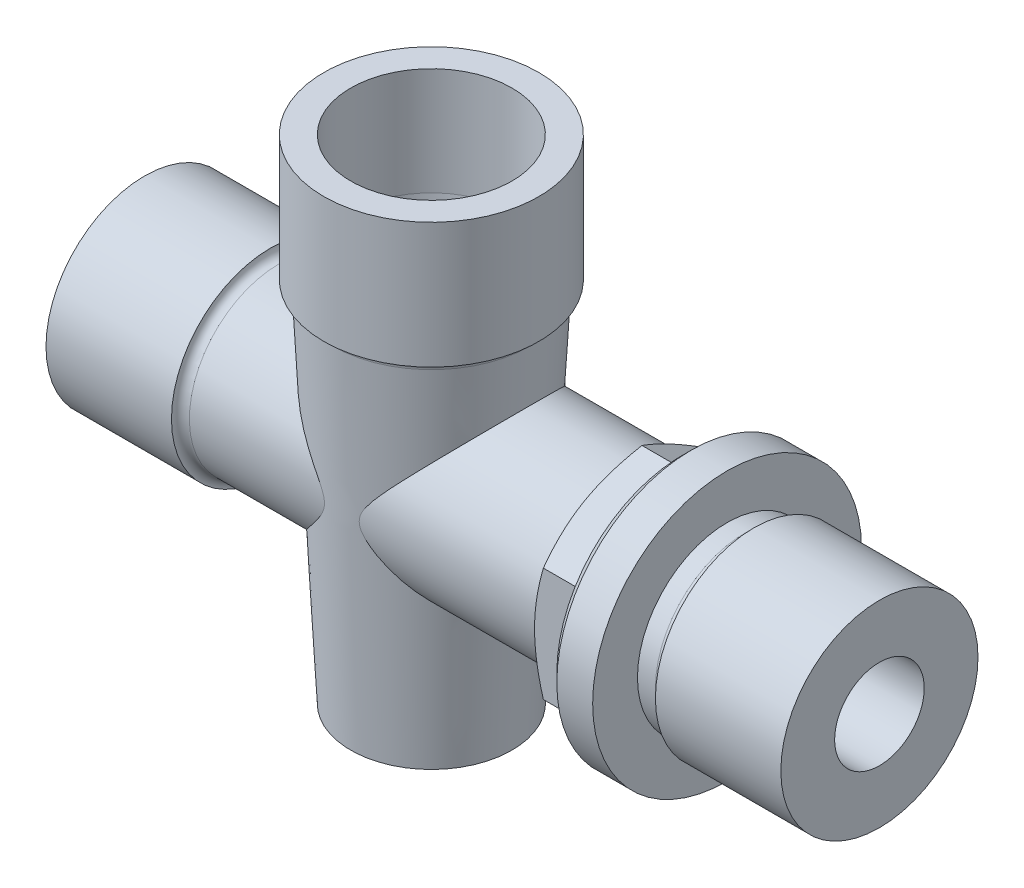
SolidWorks part; units mm, degrees
ref_plane "Спереди" through (0, 0, 0) normal (0, 0, 1) x (1, 0, 0)
ref_plane "Сверху" through (0, 0, 0) normal (0, 1, 0) x (1, 0, 0)
ref_plane "Справа" through (0, 0, 0) normal (1, 0, 0) x (0, 0, -1)
sketch "Эскиз1" plane through (0, 0, 0) normal (0, 0, 1) x (1, 0, 0)
  line L0 (0, 0) -> (0, 55) construction
  line L1 (0, 0) -> (-9, 0)
  line L2 (0, 55) -> (-9, 55) construction
  line L3 (-9, 55) -> (-12, 55)
  line L4 (-12, 55) -> (-12, 41)
  line L6 (-9, 55) -> (-9, 43)
  line L7 (0, 0) -> (0, 5)
  line L8 (-12, 41) -> (-12, 39.8607) construction
  line L9 (0, 5) -> (-7.5, 5)
  line L10 (-7.5, 5) -> (-7.5, 7)
  line L11 (-7.5, 7) -> (-5.5, 7)
  line L12 (-9, 43) -> (-5.5, 7)
  line L13 (-12, 41) -> (-12, 40) construction
  line L14 (-9, 0) -> (-11.0012, 40.0499)
  arc A0 (-11.0012, 40.0499) -> (-12, 41) centre (-12, 40) ccw
  dimension "D5" = 36
  dimension "D6" = 7.5
  dimension "D7" = 2
  dimension "D8" = 9
  dimension "D9" = 5
  dimension "D10" = 2
  dimension "D11" = 2
  dimension "D1" = 9
  dimension "D2" = 14
  dimension "D3" = 12
  dimension "D4" = 12
revolve "Повернуть1" add sketch "Эскиз1" angle 360 about L0
sketch "Эскиз2" plane through (0, 0, 0) normal (0, 0, 1) x (1, 0, 0)
  line L0 (0, 0) -> (-12.0052, 0) construction
  line L1 (0, 24) -> (-32, 24) construction
  line L2 (0, 0) -> (0, 55) construction
  line L3 (-9, 0) -> (-11.0012, 40.0499) construction
  line L4 (-32, 19) -> (0, 19)
  line L5 (-32, 24) -> (-32, 19) construction
  line L6 (-32, 19) -> (-32, 13)
  line L7 (-32, 13) -> (-18, 13)
  line L8 (-18, 13) -> (-17, 13) construction
  line L9 (-17, 14) -> (0, 14)
  line L10 (0, 14) -> (0, 19)
  arc A0 (-17, 14) -> (-18, 13) centre (-17, 13) ccw
  point P11 (-10.1993, 24)
  dimension "D5" = 11
  dimension "D6" = 1
  dimension "D1" = 24
  dimension "D2" = 32
  dimension "D3" = 5
  dimension "D4" = 14
revolve "Повернуть2" add sketch "Эскиз2" angle 360 about L1
sketch "Эскиз3" plane through (0, 0, 0) normal (0, 0, 1) x (1, 0, 0)
  line L0 (0, 0) -> (0, 24) construction
  line L1 (0, 24) -> (50, 24) construction
  line L2 (50, 24) -> (50, 29) construction
  line L3 (50, 29) -> (50, 35)
  line L4 (50, 35) -> (36, 35)
  line L5 (50, 29) -> (0, 29)
  line L6 (0, 0) -> (0, 55) construction
  line L7 (36, 35) -> (35, 35) construction
  line L8 (35, 34) -> (33, 34)
  line L9 (33, 34) -> (33, 39)
  line L10 (33, 39) -> (29, 39)
  line L11 (29, 39) -> (28, 38)
  line L12 (28, 38) -> (28, 34)
  line L13 (28, 34) -> (0, 34)
  line L14 (0, 34) -> (0, 29)
  arc A0 (35, 34) -> (36, 35) centre (35, 35) ccw
  dimension "D5" = 2
  dimension "D6" = 17
  dimension "D1" = 50
  dimension "D2" = 5
  dimension "D3" = 11
  dimension "D4" = 14
  dimension "D7" = 30
  dimension "D8" = 45
  dimension "D9" = 4
  dimension "D10" = 1
revolve "Повернуть3" add sketch "Эскиз3" angle 360 about L1
sketch "Эскиз4" plane through (28, 0, 0) normal (-1, 0, 0) x (0, 0, 1)
  line L1 (0, 36.7017) -> (-11, 30.3509)
  line L2 (-11, 30.3509) -> (-11, 17.6491)
  line L3 (-11, 17.6491) -> (0, 11.2983)
  line L4 (0, 11.2983) -> (11, 17.6491)
  line L5 (11, 17.6491) -> (11, 30.3509)
  line L6 (11, 30.3509) -> (0, 36.7017)
  circle A0 centre (0, 24) radius 5
  circle A1 centre (0, 24) radius 11 construction
  dimension "D1" = 22
extrude "Бобышка-Вытянуть1" add sketch "Эскиз4" along normal blind 6 separate body
sketch "Эскиз5" plane through (0, 0, 0) normal (0, 0, 1) x (1, 0, 0)
  line L0 (28, 11.2983) -> (28, 17.6491) construction
  line L1 (22, 17.6491) -> (22, 11.2983) construction
  line L2 (22, 11.2983) -> (28, 11.2983) construction
  line L3 (28, 30.3509) -> (28, 36.7017) construction
  line L4 (28, 36.7017) -> (22, 36.7017) construction
  line L5 (22, 36.7017) -> (22, 30.3509) construction
  line L6 (28, 17.6491) -> (28, 30.3509) construction
  line L7 (22, 30.3509) -> (22, 17.6491) construction
  line L8 (28, 11.2983) -> (28, 17.6491) construction
  line L9 (22, 17.6491) -> (22, 11.2983) construction
  line L10 (22, 11.2983) -> (28, 11.2983) construction
  line L11 (28, 30.3509) -> (28, 36.7017) construction
  line L12 (28, 36.7017) -> (23.5, 36.7017) construction
  line L13 (22, 36.7017) -> (22, 30.3509) construction
  line L14 (28, 17.6491) -> (28, 30.3509) construction
  line L15 (22, 30.3509) -> (22, 17.6491) construction
  line L16 (28, 24) -> (22, 24) construction
  line L17 (23.5, 36.7017) -> (19.6951, 30.1114)
  line L18 (17.0107, 30.1114) -> (17.0107, 41.0831)
  line L19 (17.0107, 41.0831) -> (23.5, 41.0831)
  line L20 (23.5, 41.0831) -> (23.5, 36.7017)
  line L21 (19.6951, 30.1114) -> (17.0107, 30.1114)
  dimension "D1" = 30
  dimension "D2" = 1.5
revolve "Вырез-Повернуть2" cut sketch "Эскиз5" angle 360 about L16
combine bodies "Соединить1" operation type add bodies to combine 107 105
sketch "Эскиз6" plane through (0, 0, 0) normal (0, 0, 1) x (1, 0, 0)
  line L0 (0, 55) -> (-9, 55)
  line L1 (-9, 55) -> (-9, 43)
  line L2 (-9, 43) -> (-5.5, 7)
  line L3 (-5.5, 7) -> (-7.5, 7)
  line L4 (-7.5, 7) -> (-7.5, 5)
  line L5 (-7.5, 5) -> (0, 5)
  line L6 (0, 5) -> (0, 55)
combine bodies "Соединить2" operation type add bodies to combine 103 104 108
revolve "Вырез-Повернуть3" cut sketch "Эскиз6" angle 360 about L0
sketch "Эскиз7" plane through (0, 0, 0) normal (0, 0, 1) x (1, 0, 0)
  line L0 (-32, 24) -> (50, 24)
  line L1 (50, 13) -> (50, 35) construction
  line L2 (-32, 24) -> (-32, 19)
  line L3 (-32, 19) -> (50, 19)
  line L4 (50, 19) -> (50, 24)
revolve "Вырез-Повернуть4" cut sketch "Эскиз7" angle 360 about L1
